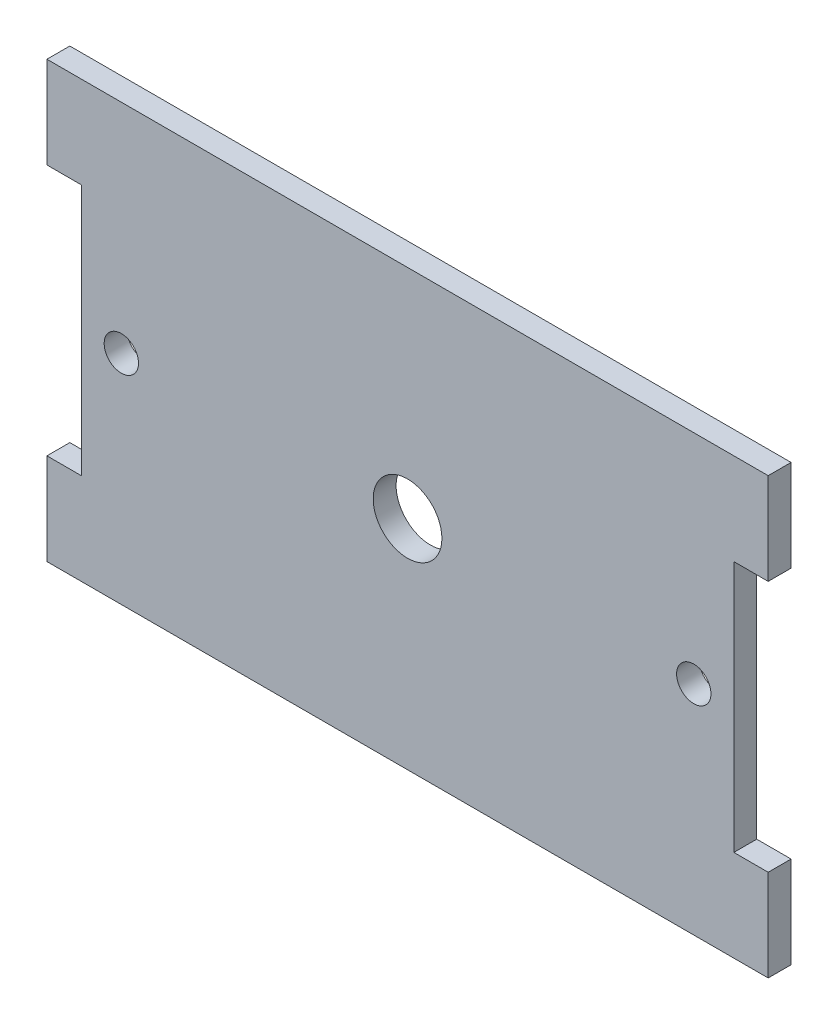
SolidWorks part; units mm, degrees
ref_plane "前视基准面" through (0, 0, 0) normal (0, 0, 1) x (1, 0, 0)
ref_plane "上视基准面" through (0, 0, 0) normal (0, 1, 0) x (1, 0, 0)
ref_plane "右视基准面" through (0, 0, 0) normal (1, 0, 0) x (0, 0, -1)
sketch "草图1" plane through (0, 0, 0) normal (0, 0, 1) x (1, 0, 0)
  line L309 (-13.2589, -46.8726) -> (-13.2589, -76.8726) construction
  line L310 (-13.2589, -46.8726) -> (-13.2589, -42.8726) construction
  line L311 (-13.2589, -42.8726) -> (-16.2589, -42.8726)
  line L312 (-16.2589, -42.8726) -> (-16.2589, -50.8726)
  line L313 (-16.2589, -50.8726) -> (-13.2589, -50.8726)
  line L314 (-13.2589, -76.8726) -> (-13.2589, -80.8726) construction
  line L315 (-13.2589, -80.8726) -> (-16.2589, -80.8726)
  line L316 (-16.2589, -80.8726) -> (-16.2589, -72.8726)
  line L317 (-16.2589, -72.8726) -> (-13.2589, -72.8726)
  line L318 (-13.2589, -72.8726) -> (-13.2589, -50.8726)
  line L322 (-13.2589, -42.8726) -> (15.2411, -42.8726)
  line L323 (15.2411, -42.8726) -> (15.2411, -80.8726) construction
  line L324 (43.7411, -76.8726) -> (43.7411, -80.8726) construction
  line L325 (43.7411, -46.8726) -> (43.7411, -42.8726) construction
  line L326 (43.7411, -46.8726) -> (43.7411, -76.8726) construction
  line L327 (43.7411, -72.8726) -> (43.7411, -50.8726)
  line L328 (46.7411, -72.8726) -> (43.7411, -72.8726)
  line L329 (46.7411, -80.8726) -> (46.7411, -72.8726)
  line L330 (43.7411, -80.8726) -> (46.7411, -80.8726)
  line L331 (46.7411, -50.8726) -> (43.7411, -50.8726)
  line L332 (46.7411, -42.8726) -> (46.7411, -50.8726)
  line L333 (43.7411, -42.8726) -> (46.7411, -42.8726)
  line L334 (15.2411, -42.8726) -> (43.7411, -42.8726)
  line L335 (43.7411, -80.8726) -> (-13.2589, -80.8726)
  line L336 (15.2411, -61.8726) -> (40.2411, -61.8726) construction
  circle A0 centre (15.2411, -61.8726) radius 3
  circle A1 centre (40.2411, -61.8726) radius 1.5
  circle A2 centre (-9.7589, -61.8726) radius 1.5
extrude "凸台-拉伸1" add sketch "草图1" along normal blind 2
sketch "草图2" plane through (0, 0, 0) normal (0, 0, -1) x (-1, 0, 0)
  line L0 (-15.2411, -61.8726) -> (-15.2411, -68.8726)
  line L1 (-15.2411, -68.8726) -> (-0.2411, -68.8726)
  line L2 (-0.2411, -68.8726) -> (-0.2411, -53.8726)
  point P0 (-15.2411, -61.8726)
